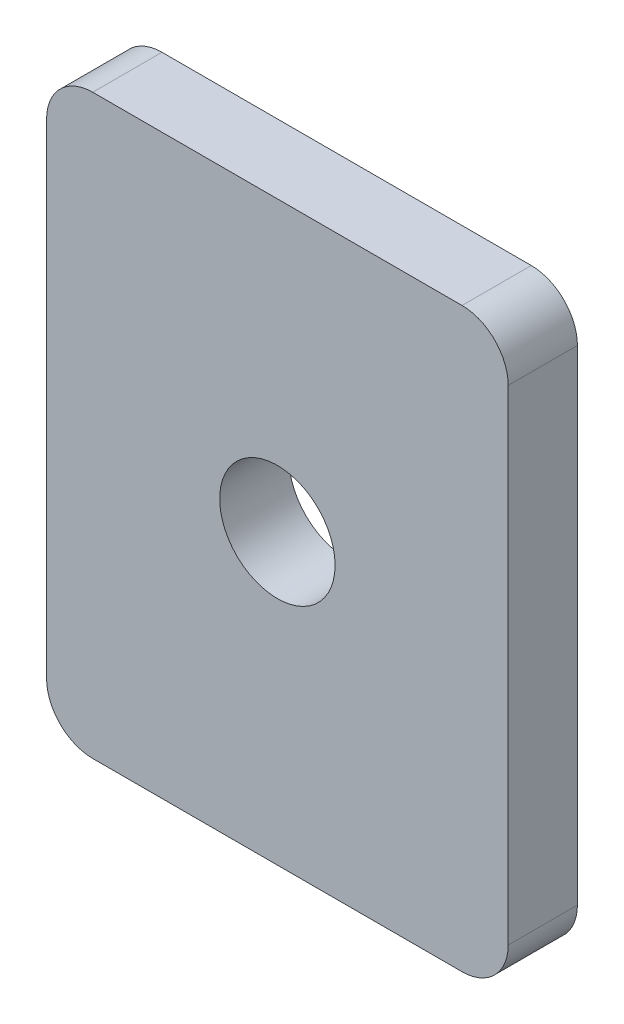
SolidWorks part; units mm, degrees
ref_plane "Plan de face" through (0, 0, 0) normal (0, 0, 1) x (1, 0, 0)
ref_plane "Plan de dessus" through (0, 0, 0) normal (0, 1, 0) x (1, 0, 0)
ref_plane "Plan de droite" through (0, 0, 0) normal (1, 0, 0) x (0, 0, -1)
sketch "Esquisse1" plane through (0, 0, 0) normal (0, 0, 1) x (1, 0, 0)
  line L0 (0, 21.9985) -> (0, -27.9896) construction
  line L1 (10, -12.5) -> (-10, -12.5)
  line L2 (10, -12.5) -> (10, 12.5)
  line L3 (10, 12.5) -> (-10, 12.5)
  line L4 (-10, -12.5) -> (-10, 12.5)
  line L5 (10, -12.5) -> (-10, 12.5) construction
  line L6 (10, 12.5) -> (-10, -12.5) construction
  circle A0 centre (0, 0) radius 2.5
  point P0 (0, 0)
  dimension "D3" = 5
  dimension "D1" = 20
  dimension "D2" = 25
extrude "Boss.-Extru.1" add sketch "Esquisse1" along normal blind 3
fillet "Congé1" radius 2 4 edges at (-10, -12.5, 1.5) (10, -12.5, 1.5) (10, 12.5, 1.5) (-10, 12.5, 1.5)
